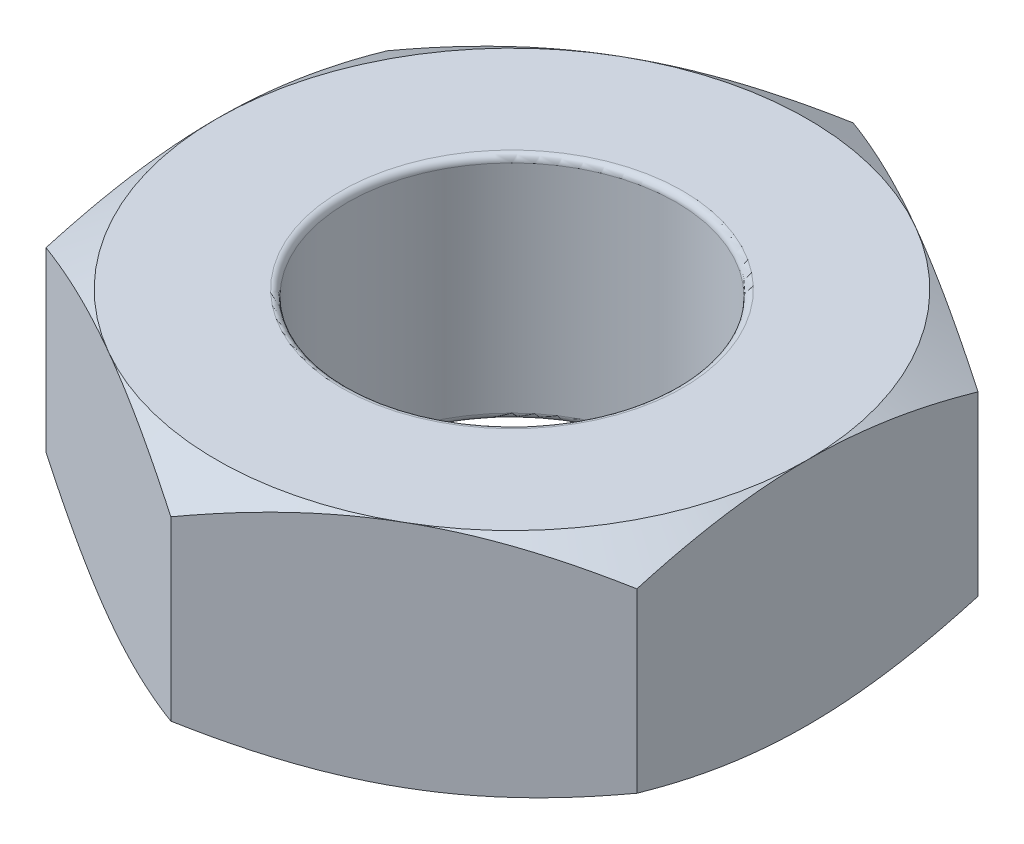
SolidWorks part; units mm, degrees
ref_plane "Front Plane" through (0, 0, 0) normal (0, 0, 1) x (1, 0, 0)
ref_plane "Top Plane" through (0, 0, 0) normal (0, 1, 0) x (1, 0, 0)
ref_plane "Right Plane" through (0, 0, 0) normal (1, 0, 0) x (0, 0, -1)
sketch "Sketch1" plane through (0, 0, 0) normal (0, 1, 0) x (1, 0, 0)
  line L1 (0, 2.5981) -> (-2.25, 1.299)
  line L2 (-2.25, 1.299) -> (-2.25, -1.299)
  line L3 (-2.25, -1.299) -> (0, -2.5981)
  line L4 (0, -2.5981) -> (2.25, -1.299)
  line L5 (2.25, -1.299) -> (2.25, 1.299)
  line L6 (2.25, 1.299) -> (0, 2.5981)
  circle A0 centre (0, 0) radius 1.25
  circle A1 centre (0, 0) radius 2.25 construction
  dimension "D1" = 2.5
  dimension "D2" = 4.5
extrude "Boss-Extrude1" add sketch "Sketch1" along normal blind 1.75
sketch "Sketch2" plane through (0, 1.75, 0) normal (0, 1, 0) x (1, 0, 0)
  circle A0 centre (0, 0) radius 2.25 construction
  circle A1 centre (0, 0) radius 2.25
extrude "Cut-Extrude1" cut sketch "Sketch2" against normal blind 2 draft 60 flip side to cut
sketch "Sketch3" plane through (0, 0, 0) normal (0, -1, 0) x (1, 0, 0)
  circle A0 centre (0, 0) radius 2.25 construction
  circle A1 centre (0, 0) radius 2.25
extrude "Cut-Extrude2" cut sketch "Sketch3" against normal blind 2 draft 60 flip side to cut
fillet "Fillet1" radius 0.05 2 edges at (0, 0, 1.25) (0, 1.75, 1.25)
